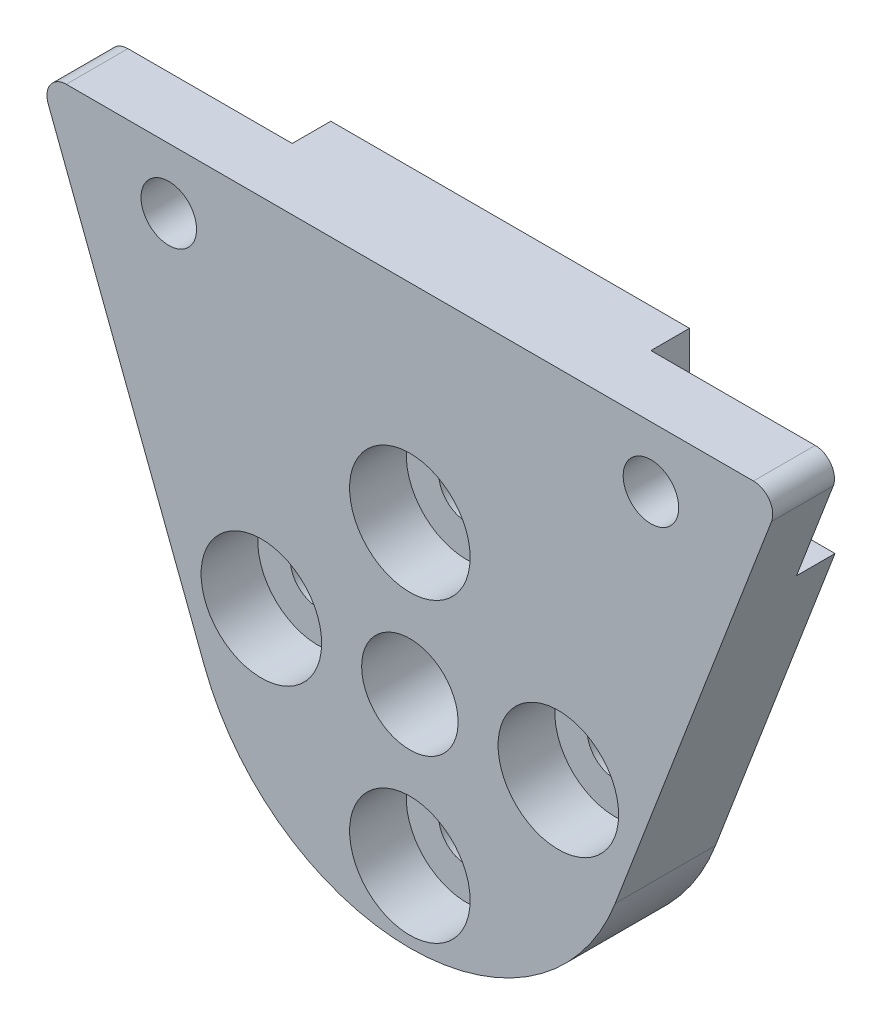
SolidWorks part; units mm, degrees
ref_plane "Front Plane" through (0, 0, 0) normal (0, 0, 1) x (1, 0, 0)
ref_plane "Top Plane" through (0, 0, 0) normal (0, 1, 0) x (1, 0, 0)
ref_plane "Right Plane" through (0, 0, 0) normal (1, 0, 0) x (0, 0, -1)
sketch "Sketch2" plane through (0, 0, 0) normal (0, 0, 1) x (1, 0, 0)
  line L0 (24.4729, 18.9865) -> (13.5236, -9.6562)
  line L1 (24.4729, 18.9865) -> (-24.4729, 18.9865)
  line L2 (0, 18.9865) -> (0, -18.9645) construction
  line L5 (-24.4729, -18.9865) -> (24.4729, 18.9865) construction
  line L6 (-24.4729, 18.9865) -> (24.4729, -18.9865) construction
  line L7 (-24.4729, 18.9865) -> (-13.5236, -9.6562)
  circle A0 centre (0, -4.4865) radius 3.175
  arc A1 (-13.5236, -9.6562) -> (13.5236, -9.6562) centre (0, -4.4865) ccw
  point P0 (0, 0)
  dimension "D3" = 6.35
  dimension "D4" = 14.478
  dimension "D1" = 37.973
  dimension "D2" = 48.9458
  dimension "D5" = 13.5236
extrude "Boss-Extrude1" add sketch "Sketch2" along normal blind 6.604
hole_wizard "CBORE for #6 Binding Head Machine Screw1" positions "Sketch3" profile "Sketch5" counterbore size "#6" standard "ANSI Inch" end condition through all
sketch "Sketch3" plane through (0, 0, 6.604) normal (0, 0, 1) x (1, 0, 0)
  line L0 (0, -4.4865) -> (0, 5.2925) construction
  line L2 (0, -4.4865) -> (9.779, -4.4865) construction
  line L3 (0, -4.4865) -> (-9.779, -4.4865) construction
  line L4 (0, -4.4865) -> (0, -14.2655) construction
  point P1 (0, 5.2925)
  point P8 (9.779, -4.4865)
  point P11 (-9.779, -4.4865)
  point P14 (0, -14.2655)
  dimension "D1" = 9.779
sketch "Sketch5" plane through (0, -14.2655, 6.604) normal (1, 0, 0) x (0, -1, 0)
  line L0 (0, 0) -> (0, 6.604)
  line L1 (0, 6.604) -> (1.8288, 6.604)
  line L3 (1.8288, 6.604) -> (1.8288, 3.7338)
  line L4 (1.8288, 3.7338) -> (3.9688, 3.7338)
  line L5 (3.9688, 3.7338) -> (3.9688, 0)
  line L7 (3.9688, 0) -> (0, 0)
  line L11 (0, -6.35) -> (0, 107.95) construction
  dimension "Thru Hole Dia." = 3.6576
  dimension "Thru Hole Depth" = 6.604
  dimension "C'Bore Dia." = 7.9375
  dimension "C'Bore Depth" = 3.7338
hole_wizard "#6 Clearance Hole1" positions "Sketch6" profile "Sketch8" hole size "#6" standard "ANSI Inch" end condition through all
sketch "Sketch6" plane through (0, 0, 0) normal (0, 0, -1) x (-1, 0, 0)
  line L0 (-22.9485, 14.9987) -> (22.9485, 14.9987) construction
  line L1 (-13.5236, -9.6562) -> (-24.4729, 18.9865) construction
  line L2 (24.4729, 18.9865) -> (13.5236, -9.6562) construction
  line L4 (-24.4729, 18.9865) -> (24.4729, 18.9865) construction
  line L5 (0, 18.9865) -> (0, -18.9645) construction
  arc A0 (-13.5236, -9.6562) -> (13.5236, -9.6562) centre (0, -4.4865) ccw construction
  point P17 (-15.875, 14.9987)
  point P19 (15.875, 14.9987)
  dimension "D1" = 3.9878
  dimension "D2" = 15.875
  dimension "D3" = 15.875
sketch "Sketch8" plane through (-15.875, 14.9987, 0) normal (1, 0, 0) x (0, 1, 0)
  line L0 (0, 0) -> (0, 6.604)
  line L1 (0, 6.604) -> (1.8288, 6.604)
  line L2 (1.8288, 6.604) -> (1.8288, 0)
  line L5 (1.8288, 0) -> (0, 0)
  line L11 (0, -6.35) -> (0, 107.95) construction
  dimension "Thru Hole Dia." = 3.6576
  dimension "Thru Hole Depth" = 6.604
sketch "Sketch9" plane through (0, 0, 0) normal (0, 0, -1) x (-1, 0, 0)
  line L0 (-11.811, 14.9987) -> (-11.811, 18.9865)
  line L1 (-24.4729, 18.9865) -> (24.4729, 18.9865) construction
  line L2 (-15.875, 10.9347) -> (-21.3949, 10.9347)
  line L3 (-13.5236, -9.6562) -> (-24.4729, 18.9865) construction
  line L4 (11.811, 14.9987) -> (11.811, 18.9865)
  line L5 (15.875, 10.9347) -> (21.3949, 10.9347)
  line L6 (24.4729, 18.9865) -> (13.5236, -9.6562) construction
  line L7 (-11.811, 18.9865) -> (-24.4729, 18.9865)
  line L8 (-24.4729, 18.9865) -> (-21.3949, 10.9347)
  line L9 (11.811, 18.9865) -> (24.4729, 18.9865)
  line L10 (24.4729, 18.9865) -> (21.3949, 10.9347)
  arc A0 (-15.875, 10.9347) -> (-11.811, 14.9987) centre (-15.875, 14.9987) ccw
  arc A1 (11.811, 14.9987) -> (15.875, 10.9347) centre (15.875, 14.9987) ccw
  dimension "D1" = 8.128
extrude "Cut-Extrude1" cut sketch "Sketch9" against normal blind 2.54
fillet "Fillet1" radius 1.27 2 edges at (24.4729, 18.9865, 4.572) (-24.4729, 18.9865, 4.572)
